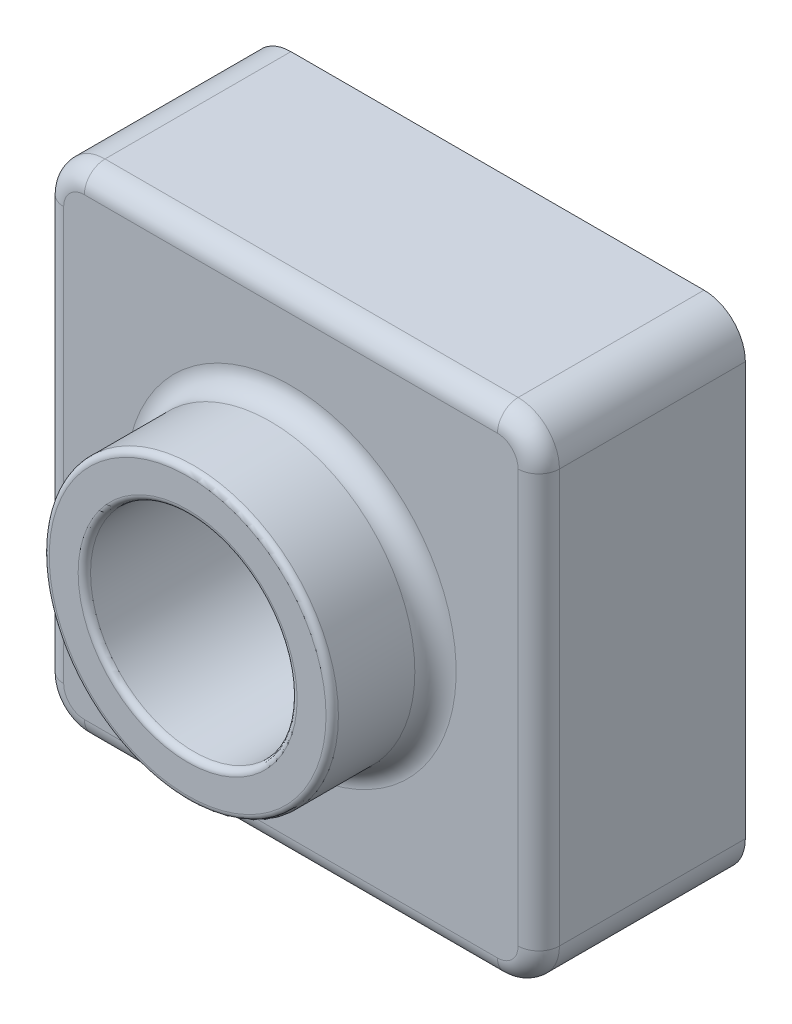
SolidWorks part; units mm, degrees
material "Copper"
ref_plane "Front Plane" through (0, 0, 0) normal (0, 0, 1) x (1, 0, 0)
ref_plane "Top Plane" through (0, 0, 0) normal (0, 1, 0) x (1, 0, 0)
ref_plane "Right Plane" through (0, 0, 0) normal (1, 0, 0) x (0, 0, -1)
sketch "Sketch9" plane through (0, 0, 0) normal (0, 0, 1) x (1, 0, 0)
  line L1 (0, 0) -> (120, 0)
  line L2 (0, 0) -> (0, 120)
  line L3 (0, 120) -> (120, 120)
  line L4 (120, 0) -> (120, 120)
  dimension "D1" = 120
  dimension "D2" = 120
extrude "Boss-Extrude6" add sketch "Sketch9" along normal blind 50
sketch "Sketch10" plane through (0, 0, 50) normal (0, 0, 1) x (1, 0, 0)
  line L0 (120, 120) -> (0, 120) construction
  line L1 (120, 0) -> (120, 120) construction
  circle A0 centre (60, 60) radius 35
  dimension "D1" = 70
  dimension "D2" = 60
  dimension "D3" = 60
extrude "Boss-Extrude7" add sketch "Sketch10" along normal blind 25
sketch "Sketch11" plane through (0, 0, 75) normal (0, 0, 1) x (1, 0, 0)
  circle A0 centre (60, 60) radius 25
  dimension "D1" = 50
extrude "Cut-Extrude3" cut sketch "Sketch11" against normal through all
fillet "Fillet5" radius 10 4 edges at (0, 120, 25) (120, 120, 25) (120, 0, 25) (0, 0, 25)
fillet "Fillet6" radius 1.5 2 edges at (95, 60, 75) (85, 60, 75)
fillet "Fillet7" radius 5 9 edges at (117.0711, 117.0711, 50) (120, 60, 50) (117.0711, 2.9289, 50) (60, 0, 50) (2.9289, 2.9289, 50) (0, 60, 50) (2.9289, 117.0711, 50) (60, 120, 50) (95, 60, 50)
shell "Shell3" thickness 2
